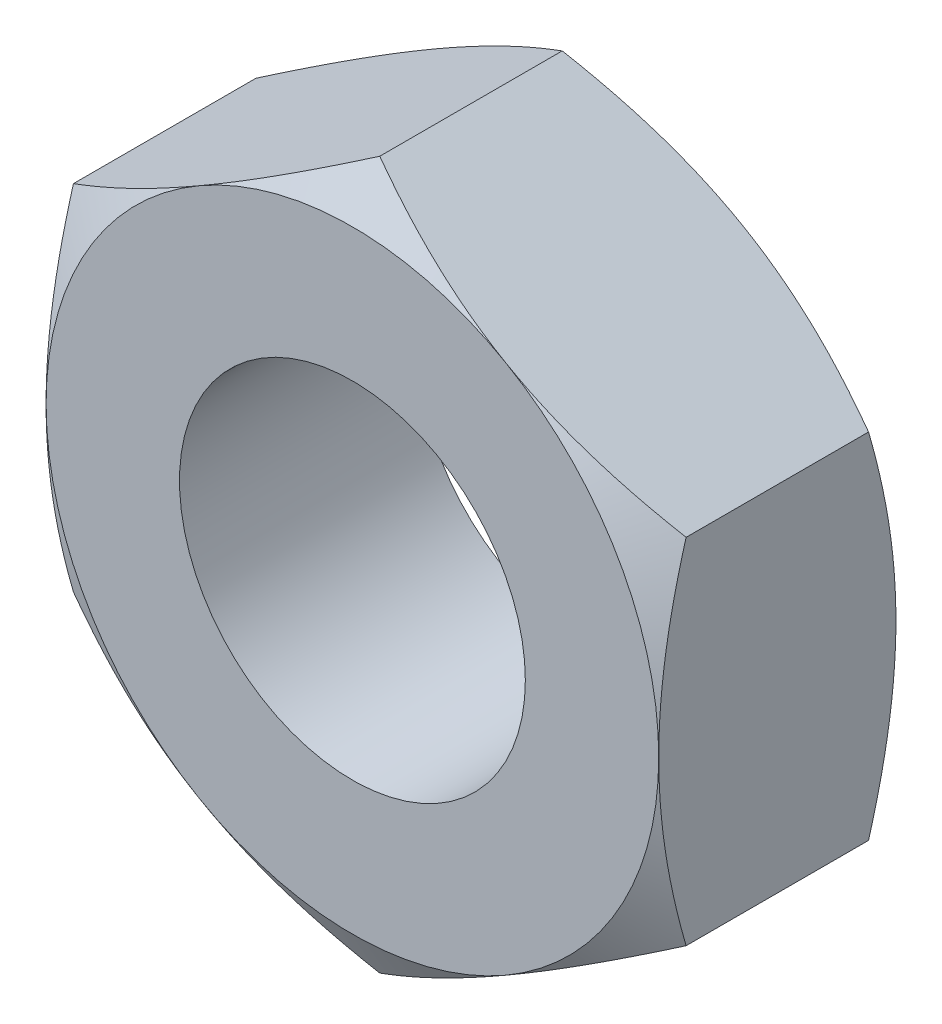
SolidWorks part; units mm, degrees
ref_plane "前基準面" through (0, 0, 0) normal (0, 0, 1) x (1, 0, 0)
ref_plane "上基準面" through (0, 0, 0) normal (0, 1, 0) x (1, 0, 0)
ref_plane "右基準面" through (0, 0, 0) normal (1, 0, 0) x (0, 0, -1)
sketch "草圖1" plane through (0, 0, 0) normal (0, 0, 1) x (1, 0, 0)
  line L0 (0, 0) -> (0, 3.5796) construction
  line L1 (0, 3.5796) -> (-3.1, 1.7898)
  line L2 (-3.1, 1.7898) -> (-3.1, -1.7898)
  line L3 (-3.1, -1.7898) -> (0, -3.5796)
  line L4 (0, -3.5796) -> (3.1, -1.7898)
  line L5 (3.1, -1.7898) -> (3.1, 1.7898)
  line L6 (3.1, 1.7898) -> (0, 3.5796)
  circle A0 centre (0, 0) radius 3.1 construction
  dimension "D1" = 6.2
extrude "伸長1" add sketch "草圖1" along normal blind 2.4
sketch "草圖2" plane through (0, 0, 2.4) normal (0, 0, 1) x (1, 0, 0)
  line L0 (3.1, 1.7898) -> (0, 3.5796) construction
  circle A0 centre (0, 0) radius 3.1
extrude "伸長2" cut sketch "草圖2" against normal blind 1.5 draft 60 flip side to cut
ref_plane "平面1" through (0, 0, 1.2) normal (0, 0, -1) x (-1, 0, 0)
mirror "鏡射1" about plane through (0, 0, 1.2) normal (0, 0, -1) of "伸長2"
sketch "草圖3" plane through (0, 0, 2.4) normal (0, 0, 1) x (1, 0, 0)
  circle A0 centre (0, 0) radius 1.75
  dimension "D1" = 3.5
extrude "伸長3" cut sketch "草圖3" against normal through all
